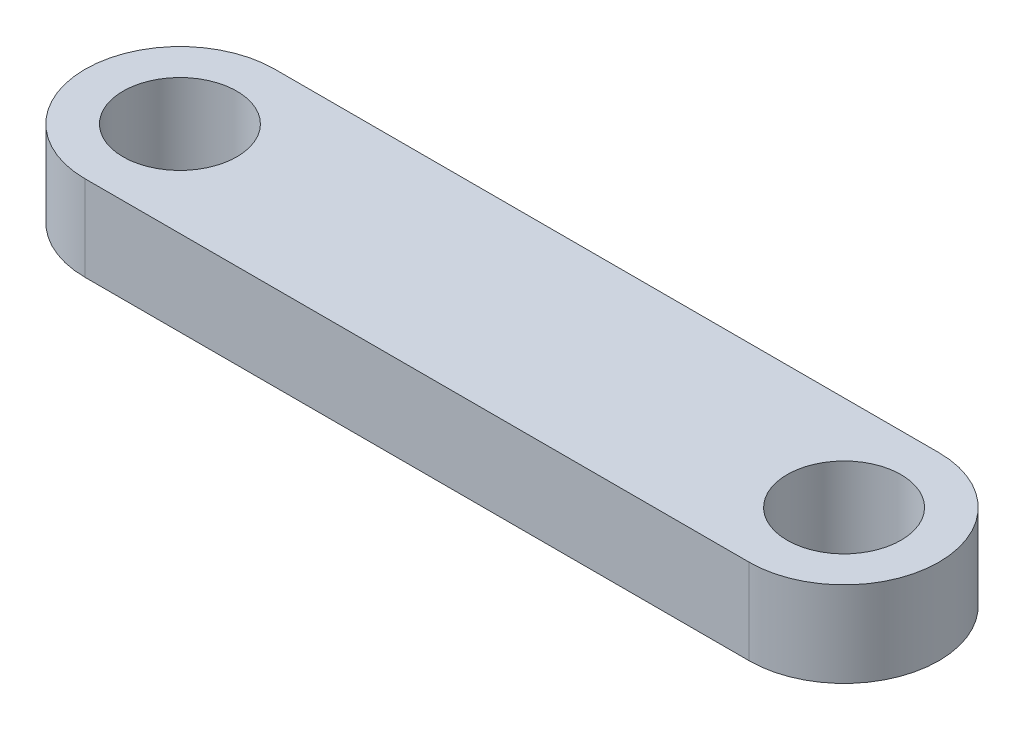
SolidWorks part; units mm, degrees
ref_plane "前视基准面" through (0, 0, 0) normal (0, 0, 1) x (1, 0, 0)
ref_plane "上视基准面" through (0, 0, 0) normal (0, 1, 0) x (1, 0, 0)
ref_plane "右视基准面" through (0, 0, 0) normal (1, 0, 0) x (0, 0, -1)
sketch "草图1" plane through (0, 0, 0) normal (0, 1, 0) x (1, 0, 0)
  line L1 (-10, 5) -> (25, 5)
  line L3 (-10, -5) -> (25, -5)
  line L6 (0, 0) -> (25, 5) construction
  arc A0 (-10, 5) -> (-10, -5) centre (-10, 0) ccw
  arc A1 (25, -5) -> (25, 5) centre (25, 0) ccw
  circle A2 centre (-10, 0) radius 3
  circle A3 centre (25, 0) radius 3
  point P0 (0, 0)
  dimension "D3" = 6
  dimension "D4" = 6
  dimension "D1" = 35
  dimension "D2" = 10
extrude "凸台-拉伸1" add sketch "草图1" along normal blind 4.5
